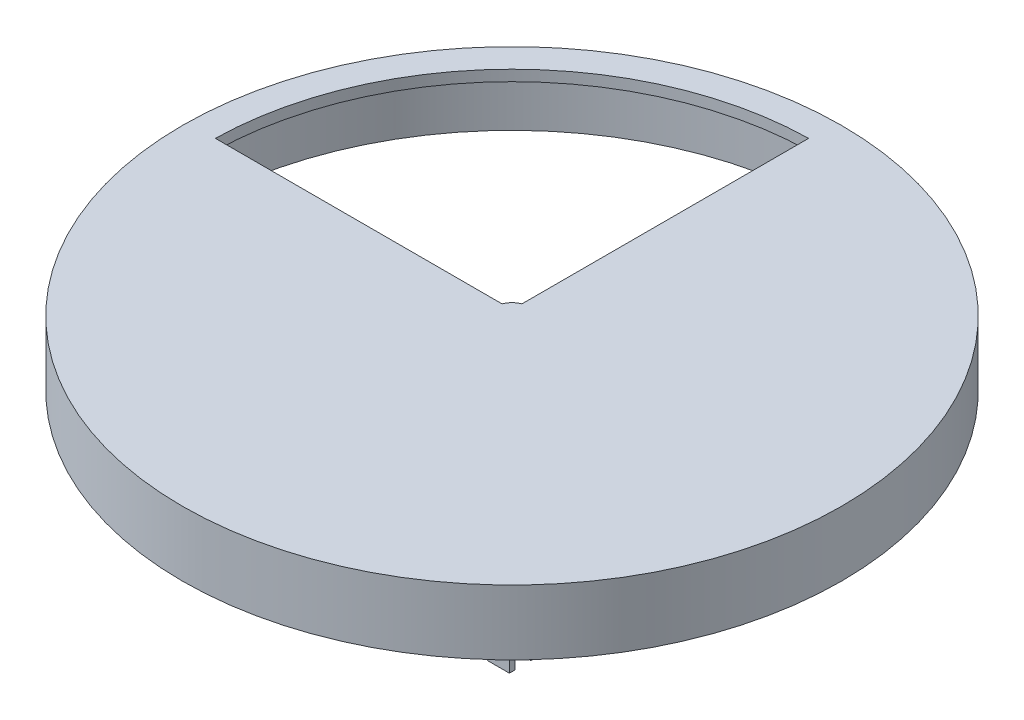
SolidWorks part; units mm, degrees
ref_plane "Plan de face" through (0, 0, 0) normal (0, 0, 1) x (1, 0, 0)
ref_plane "Plan de dessus" through (0, 0, 0) normal (0, 1, 0) x (1, 0, 0)
ref_plane "Plan de droite" through (0, 0, 0) normal (1, 0, 0) x (0, 0, -1)
sketch "Esquisse1" plane through (0, 0, 0) normal (0, 1, 0) x (1, 0, 0)
  circle A1 centre (0, 0) radius 61
extrude "Boss.-Extru.1" add sketch "Esquisse1" along normal blind 2
sketch "Esquisse2" plane through (0, 0, 0) normal (0, -1, 0) x (-1, 0, 0)
  circle A0 centre (0, 0) radius 59
  circle A1 centre (0, 0) radius 61
extrude "Boss.-Extru.2" add sketch "Esquisse2" along normal blind 10
sketch "Esquisse3" plane through (0, 0, 0) normal (0, -1, 0) x (-1, 0, 0)
  circle A0 centre (0, 0) radius 3
  circle A1 centre (0, 0) radius 2.5
extrude "Boss.-Extru.3" add sketch "Esquisse3" along normal blind 10 contours A0
sketch "Esquisse4" plane through (0, -10, 0) normal (0, -1, 0) x (-1, 0, 0)
  circle A0 centre (0, 0) radius 2.5
sketch "Esquisse5" plane through (0, 2, 0) normal (0, 1, 0) x (1, 0, 0)
  line L2 (-1, 55.8835) -> (-1, 2.8284)
  line L3 (-2.8284, 1) -> (-55.8835, 1)
  line L14 (-1, 60.9405) -> (-1.0005, 60.9409)
  line L15 (-1.0005, 60.9409) -> (-1.0002, 60.9407)
  arc A3 (-2.8284, 1) -> (-1, 2.8284) centre (0, 0) cw
  arc A4 (-55.8835, 1) -> (-1, 55.8835) centre (0, 0) cw
  arc A5 (-2.8284, 1) -> (-1, 2.8284) centre (0, 0) cw
  point P1 (-1, 2.8284)
  point P2 (-2.8284, 1)
  point P6 (-55.8835, 1)
  point P7 (-1, 55.8835)
  point P8 (-1, 60.9918)
  point P9 (-39.7269, 39.3158)
  point P10 (-1, 60.9422)
  point P11 (-39.7269, 39.3158)
  point P23 (-1, 60.9407)
  point P25 (-1, 60.9407)
  point P26 (-1, 60.9406)
  point P39 (-42.3554, 42.3554)
  point P40 (-42.3554, 42.3554)
  point P41 (-1, 59.9306)
  point P42 (-59.9602, 1)
extrude "Enlèv. mat.-Extru.6" cut sketch "Esquisse5" against normal blind 10 contours A4 L3 A3 L2
sketch "Esquisse7" plane through (0, 0, 0) normal (0, -1, 0) x (-1, 0, 0)
  line L0 (2.0204, -1.5) -> (2.0204, -2.5)
  line L1 (2.0204, -2.5) -> (-2.0166, -2.5)
  line L2 (2.0204, -1.5) -> (-2.0166, -1.5)
  line L3 (-2.0166, -2.5) -> (-2.0166, -1.5)
  line L4 (-2.0071, 1.5021) -> (-2.0071, 2.5)
  line L5 (-2.0071, 1.5021) -> (1.9929, 1.5021)
  line L8 (1.6077, 2.5) -> (-2.0071, 2.5)
  line L13 (1.9929, 2.2126) -> (1.9929, 1.5021)
  circle A0 centre (0, 0) radius 3 construction
  arc A1 (1.6077, 2.5) -> (1.9929, 2.2126) centre (3.1964, 4.2277) ccw
  point P6 (0.0019, -1.5)
  point P9 (1.6077, 2.5)
  point P10 (1.9929, 2.2126)
  point P12 (1.8252, 2.3809)
extrude "Boss.-Extru.4" add sketch "Esquisse7" along normal blind 53 contours L3 L2 L0 L1 | L5 L13 A1 L8 L4
